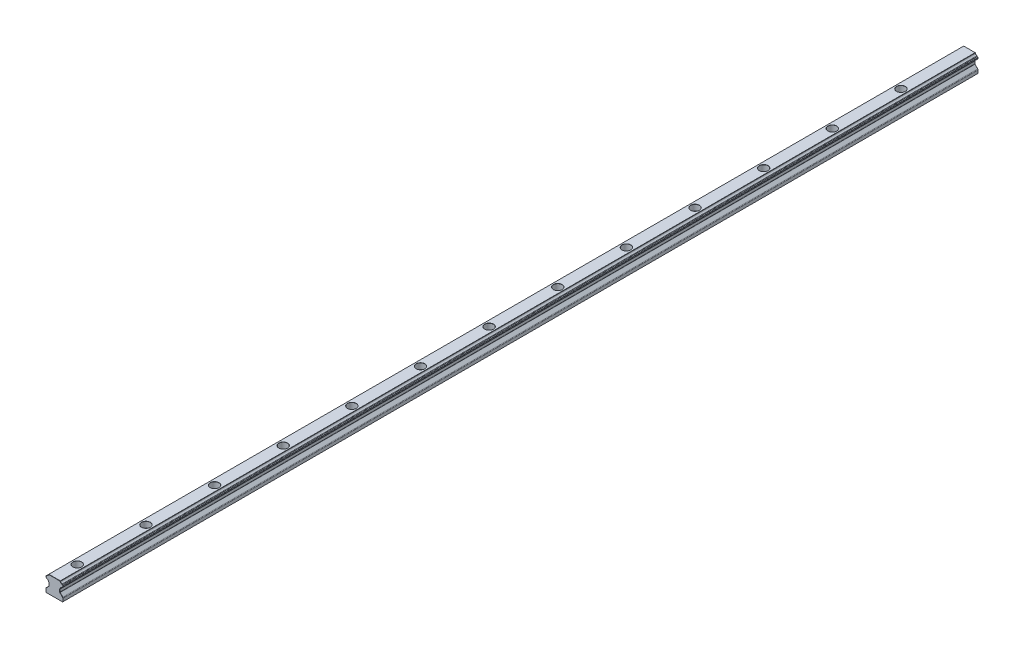
SolidWorks part; units mm, degrees
material "Plain Carbon Steel"
ref_plane "Front Plane" through (0, 0, 0) normal (0, 0, 1) x (1, 0, 0)
ref_plane "Top Plane" through (0, 0, 0) normal (0, 1, 0) x (1, 0, 0)
ref_plane "Right Plane" through (0, 0, 0) normal (1, 0, 0) x (0, 0, -1)
sketch "Rail Profile" plane through (0, 0, 0) normal (0, 0, 1) x (1, 0, 0)
  line L47 (0, 0) -> (0, 20) construction
  line L48 (-7, 0) -> (7, 0)
  line L49 (7, 0) -> (7.5, 0.5)
  line L50 (7.5, 0.5) -> (7.5, 3.0858)
  line L58 (7.2071, 3.7929) -> (4.8672, 6.1328)
  line L59 (4.75, 6.4157) -> (4.75, 8.5843)
  line L60 (4.8672, 8.8672) -> (5.063, 9.063)
  line L61 (7.5, 11.6657) -> (7.5, 12.3343)
  line L62 (-7, 0) -> (-7.5, 0.5)
  line L63 (5, 15) -> (-5, 15)
  line L64 (6.75, 9) -> (6.75, 15) construction
  line L65 (5.063, 14.937) -> (5, 15)
  line L66 (-7.5, 0.5) -> (-7.5, 3.0858)
  line L67 (6.75, 15) -> (3.75, 12) construction
  line L68 (3.75, 12) -> (6.75, 9) construction
  line L69 (7.1, 12.3343) -> (7.1, 11.6657) construction
  line L70 (6.4042, 13.0301) -> (6.4042, 10.9699) construction
  line L71 (-7.2071, 3.7929) -> (-4.8672, 6.1328)
  line L72 (-4.75, 6.4157) -> (-4.75, 8.5843)
  line L73 (-4.8672, 8.8672) -> (-5.063, 9.063)
  line L74 (5, 15) -> (8, 12) construction
  line L75 (4.8672, 8.8672) -> (8, 12) construction
  line L76 (-7.5, 11.6657) -> (-7.5, 12.3343)
  line L77 (-5.063, 14.937) -> (-5, 15)
  arc A4 (6.4734, 13.4241) -> (5.1741, 14.7234) centre (6.75, 15) cw
  arc A6 (5.1741, 9.2766) -> (6.4734, 10.5759) centre (6.75, 9) cw
  arc A7 (7.2071, 3.7929) -> (7.5, 3.0858) centre (6.5, 3.0858) cw
  arc A8 (5.063, 14.937) -> (5.1741, 14.7234) centre (4.7801, 14.6542) cw
  arc A9 (6.4734, 13.4241) -> (6.8012, 13.0792) centre (6.4042, 13.0301) cw
  arc A10 (7.1491, 12.7313) -> (7.5, 12.3343) centre (7.1, 12.3343) cw
  arc A11 (7.5, 11.6657) -> (7.1491, 11.2687) centre (7.1, 11.6657) cw
  arc A12 (6.8012, 10.9208) -> (6.4734, 10.5759) centre (6.4042, 10.9699) cw
  arc A13 (5.1741, 9.2766) -> (5.063, 9.063) centre (4.7801, 9.3458) cw
  arc A14 (4.8672, 8.8672) -> (4.75, 8.5843) centre (5.15, 8.5843) ccw
  arc A15 (4.75, 6.4157) -> (4.8672, 6.1328) centre (5.15, 6.4157) ccw
  arc A16 (6.8012, 13.0792) -> (7.1491, 12.7313) centre (7.1981, 13.1283) ccw
  arc A17 (7.1491, 11.2687) -> (6.8012, 10.9208) centre (7.1981, 10.8717) ccw
  arc A18 (-7.2071, 3.7929) -> (-7.5, 3.0858) centre (-6.5, 3.0858) ccw
  arc A19 (-4.75, 6.4157) -> (-4.8672, 6.1328) centre (-5.15, 6.4157) cw
  arc A20 (-4.8672, 8.8672) -> (-4.75, 8.5843) centre (-5.15, 8.5843) cw
  arc A21 (-5.1741, 9.2766) -> (-5.063, 9.063) centre (-4.7801, 9.3458) ccw
  arc A22 (-5.1741, 9.2766) -> (-6.4734, 10.5759) centre (-6.75, 9) ccw
  arc A23 (-6.8012, 10.9208) -> (-6.4734, 10.5759) centre (-6.4042, 10.9699) ccw
  arc A24 (-7.1491, 11.2687) -> (-6.8012, 10.9208) centre (-7.1981, 10.8717) cw
  arc A25 (-7.5, 11.6657) -> (-7.1491, 11.2687) centre (-7.1, 11.6657) ccw
  arc A26 (-7.1491, 12.7313) -> (-7.5, 12.3343) centre (-7.1, 12.3343) ccw
  arc A27 (-6.8012, 13.0792) -> (-7.1491, 12.7313) centre (-7.1981, 13.1283) cw
  arc A28 (-6.4734, 13.4241) -> (-6.8012, 13.0792) centre (-6.4042, 13.0301) ccw
  arc A29 (-6.4734, 13.4241) -> (-5.1741, 14.7234) centre (-6.75, 15) ccw
  arc A30 (-5.063, 14.937) -> (-5.1741, 14.7234) centre (-4.7801, 14.6542) ccw
  point P2 (4.75, 7.5)
  point P12 (7.5, 12)
  point P19 (6.75, 12)
  point P25 (5.1578, 14.8422)
  point P50 (8, 12)
  point P78 (0, 15)
  dimension "Rb" = 1.6
  dimension "Rf1" = 1
  dimension "Rf2" = 0.4
  dimension "WR" = 15
  dimension "Wi" = 9.5
  dimension "Wt" = 5
  dimension "Ac" = 135
  dimension "HR" = 15
  dimension "Hm" = 7.5
  dimension "Hb" = 12
  dimension "Hc" = 0.5
  dimension "Wb" = 7.5
extrude "Body" add sketch "Rail Profile" against normal blind 800
chamfer "Aesthetic Chamfer" distance 0.15 angle 45 84 edges at (-5.0315, 14.9685, 0) (-5.135, 14.8388, 0) (-5.6186, 13.8686, 0) (-6.6941, 13.3057, 0) (-6.9153, 12.8454, 0) (-7.3997, 12.5992, 0) (-7.5, 12, 0) (-7.3997, 11.4008, 0) (-6.9153, 11.1546, 0) (-6.6941, 10.6943, 0) (-5.6186, 10.1314, 0) (-5.135, 9.1612, 0) (-4.9651, 8.9651, 0) (-4.7804, 8.7374, 0) (-4.75, 7.5, 0) (-4.7804, 6.2626, 0) (-6.0371, 4.9629, 0) (-7.4239, 3.4685, 0) (-7.5, 1.7929, 0) (-7.25, 0.25, 0) (0, 0, 0) (7.25, 0.25, 0) (5.0315, 14.9685, 0) (5.135, 14.8388, 0) (5.6186, 13.8686, 0) (6.6941, 13.3057, 0) (6.9153, 12.8454, 0) (7.3997, 12.5992, 0) (7.5, 12, 0) (7.3997, 11.4008, 0) (6.9153, 11.1546, 0) (6.6941, 10.6943, 0) (5.6186, 10.1314, 0) (5.135, 9.1612, 0) (4.9651, 8.9651, 0) (4.7804, 8.7374, 0) (7.5, 1.7929, 0) (4.75, 7.5, 0) (7.4239, 3.4685, 0) (4.7804, 6.2626, 0) (6.0371, 4.9629, 0) (0, 15, 0) (5.0315, 14.9685, -800) (5.135, 14.8388, -800) (5.6186, 13.8686, -800) (6.6941, 13.3057, -800) (6.9153, 12.8454, -800) (7.3997, 12.5992, -800) (7.5, 12, -800) (7.3997, 11.4008, -800) (6.9153, 11.1546, -800) (6.6941, 10.6943, -800) (5.6186, 10.1314, -800) (5.135, 9.1612, -800) (4.9651, 8.9651, -800) (4.7804, 8.7374, -800) (4.75, 7.5, -800) (4.7804, 6.2626, -800) (6.0371, 4.9629, -800) (7.4239, 3.4685, -800) (7.5, 1.7929, -800) (7.25, 0.25, -800) (0, 0, -800) (-7.25, 0.25, -800) (-5.0315, 14.9685, -800) (-5.135, 14.8388, -800) (-5.6186, 13.8686, -800) (-6.6941, 13.3057, -800) (-6.9153, 12.8454, -800) (-7.3997, 12.5992, -800) (-7.5, 12, -800) (-7.3997, 11.4008, -800) (-6.9153, 11.1546, -800) (-6.6941, 10.6943, -800) (-5.6186, 10.1314, -800) (-7.5, 1.7929, -800) (-5.135, 9.1612, -800) (-7.4239, 3.4685, -800) (-4.9651, 8.9651, -800) (-6.0371, 4.9629, -800) (-4.7804, 8.7374, -800) (-4.7804, 6.2626, -800) (-4.75, 7.5, -800) (0, 15, -800)
hole_wizard "Mounting Hole" positions "3DSketch1" profile "Sketch1" counterbore size "M4" standard "ISO" end condition through all
sketch3d "3DSketch1"
  point P0 (0, 15, -20)
  dimension "D1" = 7.5
  dimension "E1" = 20
sketch "Sketch1" plane through (0, 15, -20) normal (1, 0, 0) x (0, 0, 1)
  line L0 (0, 0) -> (0, 15)
  line L1 (2.25, 14.9) -> (2.35, 15)
  line L2 (2.25, 14.9) -> (2.25, 5.4)
  line L3 (2.25, 5.4) -> (2.35, 5.3)
  line L4 (2.35, 5.3) -> (3.75, 5.3)
  line L5 (3.75, 5.3) -> (3.75, 0.1)
  line L6 (3.75, 0.1) -> (3.85, 0)
  line L7 (3.85, 0) -> (0, 0)
  line L8 (-3.75, 0.1) -> (-3.85, 0) construction
  line L9 (-2.25, 5.4) -> (-2.35, 5.3) construction
  line L11 (0, -6.35) -> (0, 107.95) construction
  line L12 (2.35, 15) -> (0, 15)
  line L13 (-2.25, 14.9) -> (-2.35, 15) construction
  dimension "Thru Hole Dia." = 4.5
  dimension "Thru Hole Depth" = 15
  dimension "C'Bore Dia." = 7.5
  dimension "C'Bore Depth" = 5.3
  dimension "Near C'Sink Dia." = 7.7
  dimension "Near C'Sink Angle" = 90
  dimension "Mid C'Sink Dia." = 4.7
  dimension "Mid C'Sink Angle" = 90
  dimension "Far C'Sink Dia." = 4.7
  dimension "Far C'Sink Angle" = 90
fillet "Production Fillet" radius 0.1 1 edges at (0, 9.7, -16.25)
pattern_linear "Mounting Holes Pattern" count 13 spacing 60 along (0, 0, -1) of "Mounting Hole", "Production Fillet"
equation "\"Wt@Rail Profile\"= \"WR@Rail Profile\" / 3'Top Side Half Width"
equation "\"Hm@Rail Profile\"= \"HR@Rail Profile\" / 2'Recirculation Avoidance Height"
equation "\"Hb@Rail Profile\"= 0.8 * \"HR@Rail Profile\"'Pivot Height"
equation "\"Hc@Rail Profile\"= \"WR@Rail Profile\" / 30'Chamfer Width"
equation "\"Wb@Rail Profile\"= \"WR@Rail Profile\" / 2'Ball Center Cross Width"
equation "\"D1@3DSketch1\"= \"WR@Rail Profile\" / 2'Hole Center Position"
